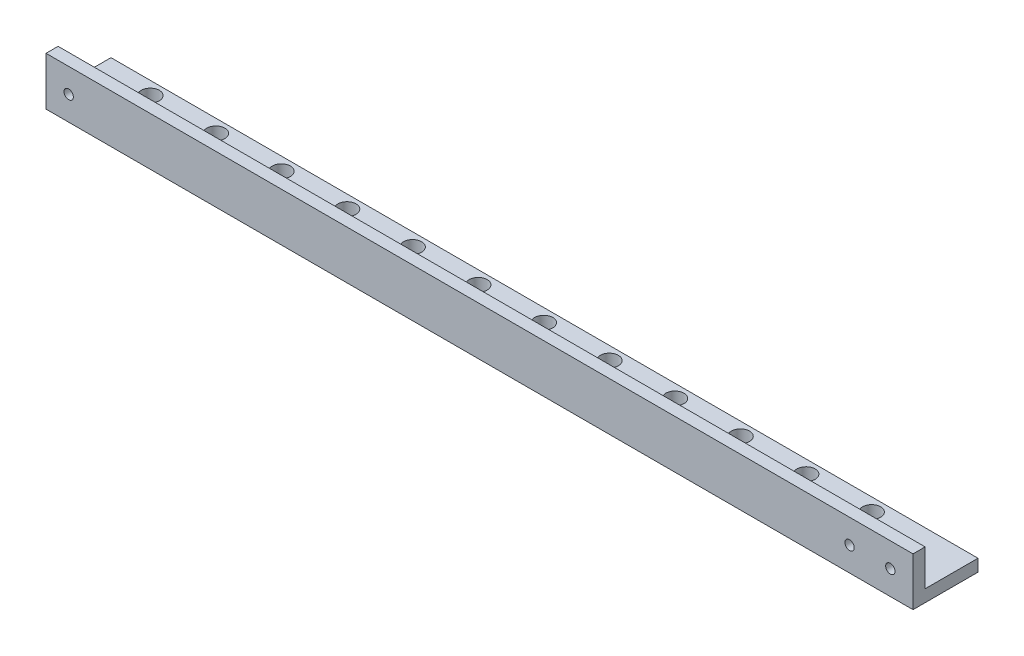
SolidWorks part; units mm, degrees
ref_plane "Front" through (0, 0, 0) normal (0, 0, 1) x (1, 0, 0)
ref_plane "Top" through (0, 0, 0) normal (0, 1, 0) x (1, 0, 0)
ref_plane "Right" through (0, 0, 0) normal (1, 0, 0) x (0, 0, -1)
sketch "Sketch1" plane through (0, 0, 0) normal (0, 1, 0) x (1, 0, 0)
  line L1 (-17.35, 4.35) -> (269.55, 4.35)
  line L2 (-17.35, 4.35) -> (-17.35, -17.15)
  line L3 (-17.35, -17.15) -> (269.55, -17.15)
  line L4 (269.55, 4.35) -> (269.55, -17.15)
  line L5 (-17.35, 4.35) -> (269.55, -17.15) construction
  line L6 (-17.35, -17.15) -> (269.55, 4.35) construction
  circle A0 centre (0, 0) radius 3
  circle A1 centre (21.7, 0) radius 3
  circle A2 centre (43.4, 0) radius 3
  circle A3 centre (65.1, 0) radius 3
  circle A4 centre (86.8, 0) radius 3
  circle A5 centre (108.5, 0) radius 3
  circle A6 centre (130.2, 0) radius 3
  circle A7 centre (151.9, 0) radius 3
  circle A8 centre (173.6, 0) radius 3
  circle A9 centre (195.3, 0) radius 3
  circle A10 centre (217, 0) radius 3
  circle A11 centre (238.7, 0) radius 3
  point P29 (126.1, -6.4)
  dimension "D1" = 6
  dimension "D3" = 21.7
  dimension "D4" = 21.5
  dimension "D5" = 17.35
  dimension "D6" = 30.85
  dimension "D7" = 4.35
  dimension "D2" = 12
extrude "Boss-Extrude1" add sketch "Sketch1" along normal blind 4
sketch "Sketch2" plane through (0, 0, 17.15) normal (0, 0, 1) x (1, 0, 0)
  line L0 (-17.35, 4) -> (-17.35, 0) construction
  line L1 (269.55, 4) -> (-17.35, 4)
  line L2 (269.55, 4) -> (269.55, 16)
  line L3 (269.55, 16) -> (-17.35, 16)
  line L4 (-17.35, 4) -> (-17.35, 16)
  line L5 (269.55, 4) -> (-17.35, 16) construction
  line L6 (269.55, 16) -> (-17.35, 4) construction
  point P4 (126.1, 10)
  dimension "D1" = 12
extrude "Boss-Extrude2" add sketch "Sketch2" against normal blind 4
sketch "Sketch6" plane through (0, 8.4088, 13.15) normal (0, 0, 1) x (-1, 0, 0)
  line L3 (-269.55, -7.5912) -> (17.35, -7.5912) construction
  line L4 (-269.55, 4.4088) -> (-269.55, -7.5912) construction
  line L5 (17.35, -7.5912) -> (17.35, 4.4088) construction
  circle A0 centre (-262.05, 0.4088) radius 1.55
  circle A1 centre (-248.55, 0.4088) radius 1.55
  circle A2 centre (9.85, 0.4088) radius 1.55
  dimension "D1" = 3.1
  dimension "D2" = 3.1
  dimension "D3" = 7.5
  dimension "D4" = 13.5
  dimension "D5" = 8
  dimension "D6" = 3.1
  dimension "D7" = 7.5
extrude "Cut-Extrude4" cut sketch "Sketch6" along normal through all
